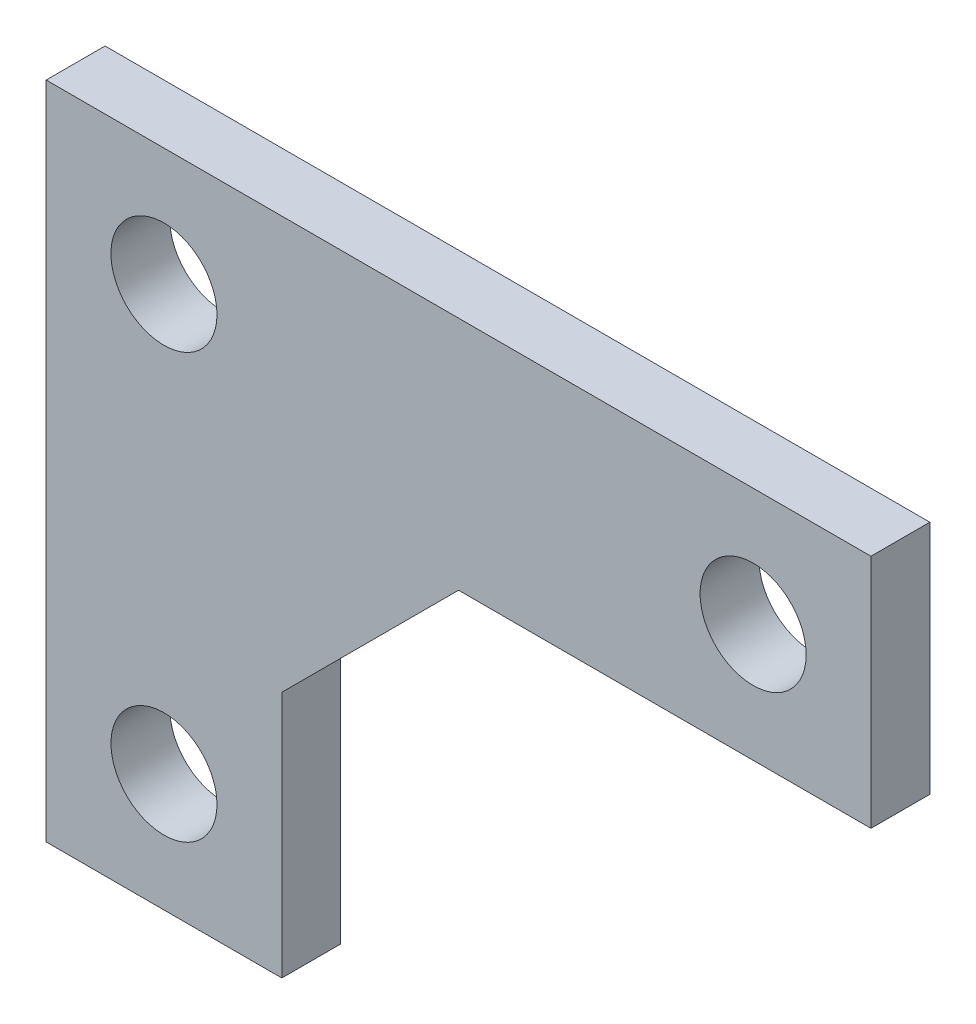
SolidWorks part; units mm, degrees
ref_plane "前视基准面" through (0, 0, 0) normal (0, 0, 1) x (1, 0, 0)
ref_plane "上视基准面" through (0, 0, 0) normal (0, 1, 0) x (1, 0, 0)
ref_plane "右视基准面" through (0, 0, 0) normal (1, 0, 0) x (0, 0, -1)
sketch "草图1" plane through (0, 0, 0) normal (0, 0, 1) x (1, 0, 0)
  line L0 (0, 0) -> (0, 36) construction
  line L15 (-10, 26) -> (-10, 10)
  line L16 (-10, 46) -> (10, 46)
  line L21 (-10, 46) -> (-10, 26)
  line L24 (-10, 46) -> (10, 26) construction
  line L25 (-10, 26) -> (10, 46) construction
  line L27 (-10, 10) -> (-10, -10)
  line L28 (-10, -10) -> (10, -10)
  line L29 (10, 10) -> (10, -10)
  line L30 (-10, 10) -> (10, -10) construction
  line L31 (-10, -10) -> (10, 10) construction
  line L32 (10, 26) -> (10, 10)
  line L33 (0, 36) -> (50, 36) construction
  line L34 (10, 46) -> (40, 46)
  line L35 (40, 46) -> (60, 46)
  line L37 (40, 26) -> (60, 26)
  line L38 (60, 46) -> (60, 26)
  line L39 (40, 46) -> (60, 26) construction
  line L40 (40, 26) -> (60, 46) construction
  line L41 (10, 26) -> (40, 26)
  circle A0 centre (0, 0) radius 4.5
  circle A4 centre (0, 36) radius 4.5
  circle A5 centre (50, 36) radius 4.5
extrude "凸台-拉伸1" add sketch "草图1" against normal blind 5
chamfer "倒角1" distance 15 angle 45 1 edges at (10, 26, -2.5)
